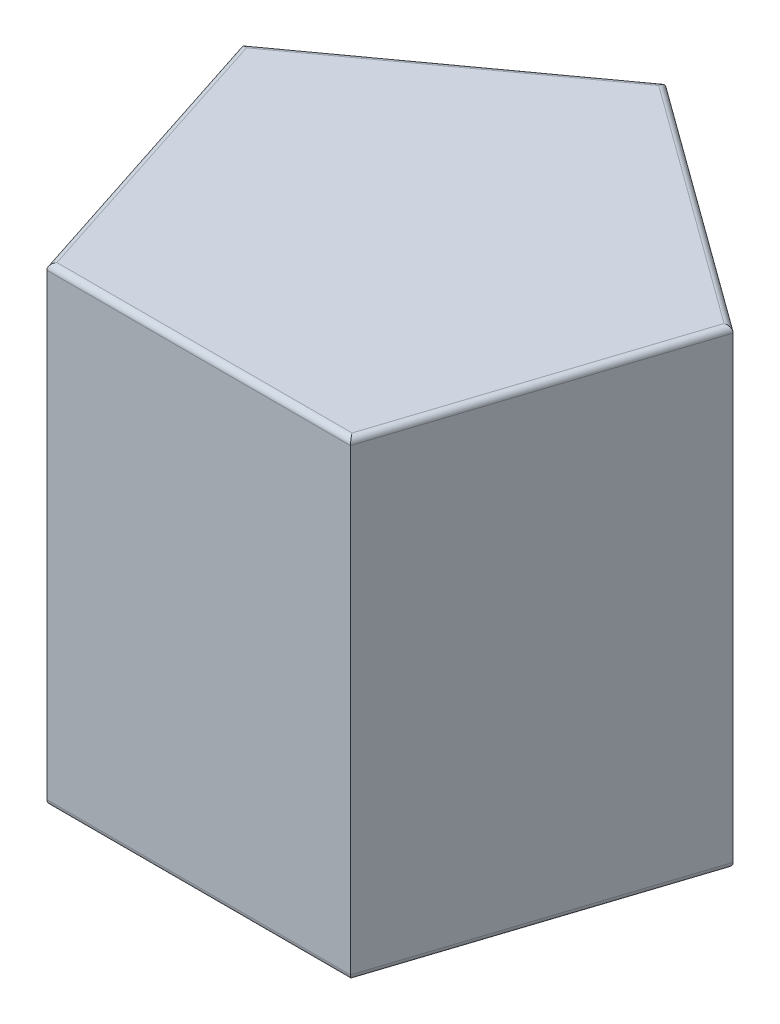
SolidWorks part; units mm, degrees
ref_plane "Front Plane" through (0, 0, 0) normal (1, 0, 0) x (0, 1, 0)
ref_plane "Top Plane" through (0, 0, 0) normal (0, 0, 1) x (0, 1, 0)
ref_plane "Right Plane" through (0, 0, 0) normal (0, 1, 0) x (-1, 0, 0)
sketch "Sketch1" plane through (0, 0, 0) normal (0, 1, 0) x (-1, 0, 0)
  line L0 (12.9201, 17.783) -> (20.9051, -6.7925)
  line L1 (20.9051, -6.7925) -> (0, -21.981)
  line L2 (0, -21.981) -> (-20.9051, -6.7925)
  line L3 (-20.9051, -6.7925) -> (-12.9201, 17.783)
  line L4 (-12.9201, 17.783) -> (12.9201, 17.783)
extrude "Boss-Extrude1" add sketch "Sketch1" along normal blind 40
fillet "Fillet1" radius 0.5 10 edges at (0, 0, 17.783) (16.9126, 0, 5.4952) (10.4526, 0, -14.3867) (-10.4526, 0, -14.3867) (-16.9126, 0, 5.4952) (0, 40, 17.783) (16.9126, 40, 5.4952) (10.4526, 40, -14.3867) (-10.4526, 40, -14.3867) (-16.9126, 40, 5.4952)
